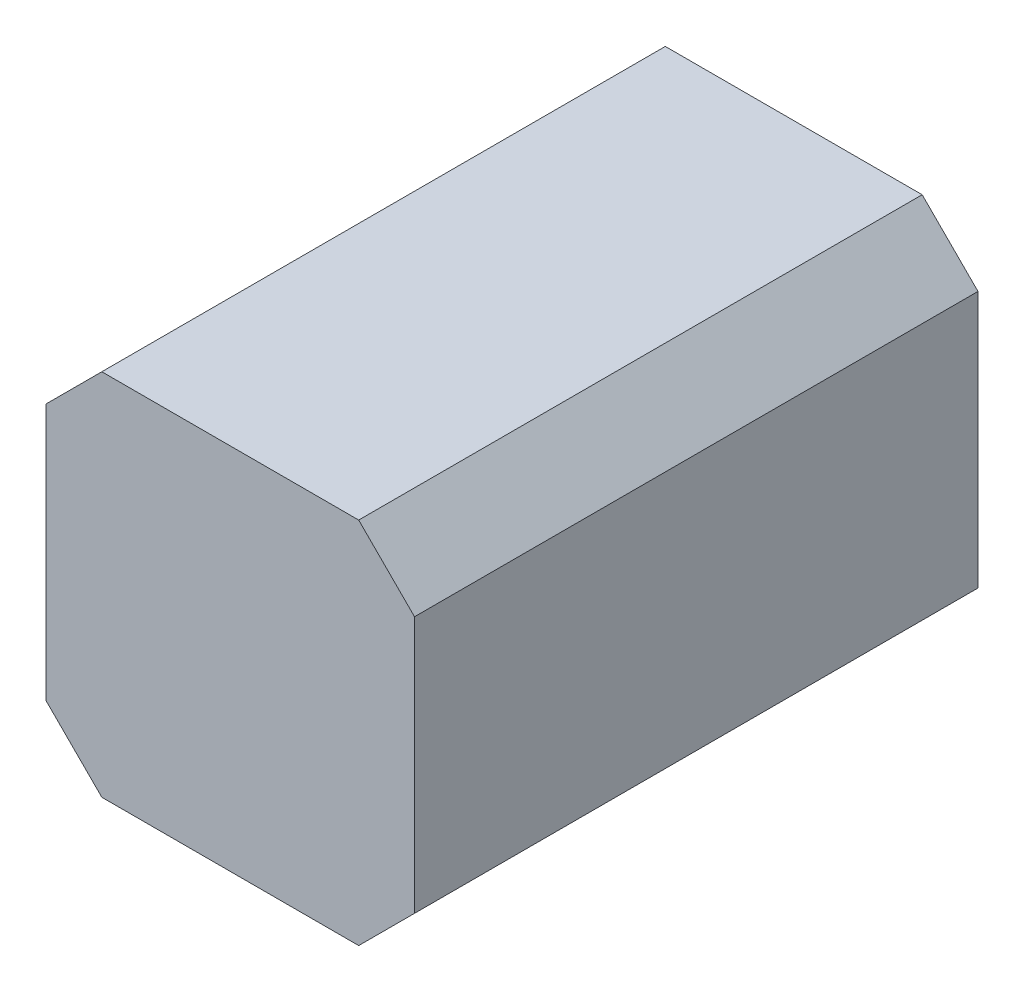
SolidWorks part; units mm, degrees
ref_plane "前视基准面" through (0, 0, 0) normal (0, 0, 1) x (1, 0, 0)
ref_plane "上视基准面" through (0, 0, 0) normal (0, 1, 0) x (1, 0, 0)
ref_plane "右视基准面" through (0, 0, 0) normal (1, 0, 0) x (0, 0, -1)
sketch "草图3" plane through (0, 0, 0) normal (0, 0, 1) x (1, 0, 0)
  line L0 (-77.5, -77.5) -> (77.5, 77.5) construction
  line L1 (-77.5, -77.5) -> (77.5, -77.5)
  line L2 (-77.5, -77.5) -> (-77.5, 77.5)
  line L3 (-77.5, 77.5) -> (77.5, 77.5)
  line L4 (77.5, -77.5) -> (77.5, 77.5)
  line L5 (54.0219, 77.5) -> (77.5, 54.0219)
  line L6 (77.5, -54.0219) -> (54.0219, -77.5)
  line L7 (-77.5, 77.5) -> (77.5, -77.5) construction
  line L8 (-77.5, 54.0219) -> (-54.0219, 77.5)
  line L9 (-54.0219, -77.5) -> (-77.5, -54.0219)
  point P0 (0, 0)
  point P15 (0, 0)
  dimension "D1" = 155
  dimension "D2" = 155
  dimension "D3" = 93
  dimension "D4" = 4
extrude "凸台-拉伸2" add sketch "草图3" along normal blind 237 contours L9 L1 L6 L4 L5 L3 L8 L2
ref_plane "基准面1" through (0, 0, 220) normal (0, 0, -1) x (-1, 0, 0)
